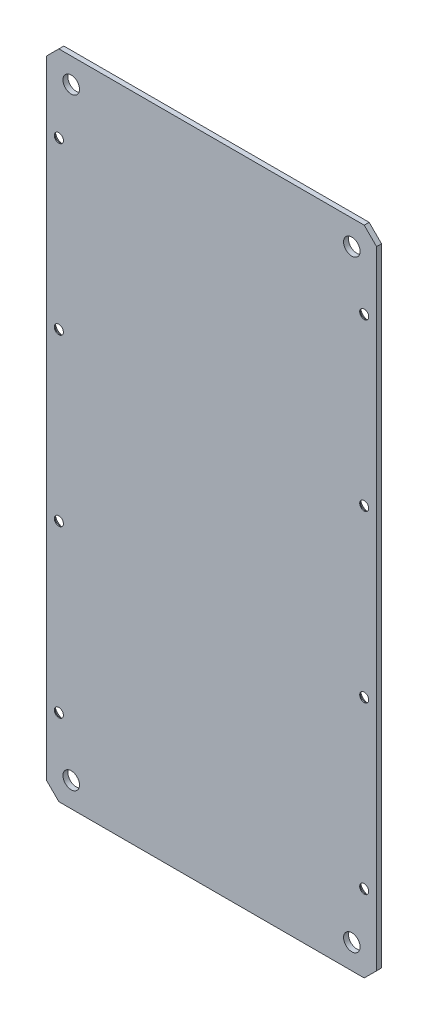
SolidWorks part; units mm, degrees
ref_plane "Спереди" through (0, 0, 0) normal (0, 0, 1) x (1, 0, 0)
ref_plane "Сверху" through (0, 0, 0) normal (0, 1, 0) x (1, 0, 0)
ref_plane "Справа" through (0, 0, 0) normal (1, 0, 0) x (0, 0, -1)
sketch "Эскиз1" plane through (0, 0, 0) normal (0, 0, 1) x (1, 0, 0)
  line L0 (0, 66.6486) -> (0, -35.3582) construction
  line L1 (-169.9255, 0) -> (185.3645, 0) construction
  line L2 (-100, 190) -> (-92.5, 197.5)
  line L3 (-92.5, -197.5) -> (92.5, -197.5)
  line L4 (-100, -190) -> (-100, 190)
  line L5 (-92.5, 197.5) -> (92.5, 197.5)
  line L6 (100, -190) -> (100, 190)
  line L7 (92.5, 197.5) -> (100, 190)
  line L8 (92.5, -197.5) -> (100, -190)
  line L9 (-100, -190) -> (-92.5, -197.5)
  line L10 (-92.5, 0) -> (-92.5, 132.1142) construction
  circle A0 centre (-85, 182.5) radius 5
  circle A1 centre (85, 182.5) radius 5
  circle A2 centre (85, -182.5) radius 5
  circle A3 centre (-85, -182.5) radius 5
  circle A5 centre (-92.5, 150.75) radius 2.75
  circle A6 centre (-92.5, -150.75) radius 2.75
  circle A7 centre (-92.5, 50.25) radius 2.75
  circle A8 centre (-92.5, -50.25) radius 2.75
  circle A9 centre (92.5, 150.75) radius 2.75
  circle A10 centre (92.5, 50.25) radius 2.75
  circle A12 centre (92.5, -50.25) radius 2.75
  circle A13 centre (92.5, -150.75) radius 2.75
  point P5 (-100, -197.5)
  point P6 (100, 197.5)
  point P7 (-100, 197.5)
  point P8 (100, -197.5)
  dimension "D3" = 10
  dimension "D4" = 15
  dimension "D12" = 5.5
  dimension "D13" = 301.5
  dimension "D6" = 100.5
  dimension "D1" = 395
  dimension "D2" = 200
  dimension "D5" = 15
  dimension "D8" = 7.5
  dimension "D9" = 7.5
  dimension "D10" = 7.5
  dimension "D11" = 7.5
  dimension "D15" = 7.5
extrude "Вытянуть1" add sketch "Эскиз1" along normal blind 3
chamfer "Фаска1" distance 2.5 angle 45 8 edges at (-89.75, 150.75, 0) (-89.75, 50.25, 0) (-95.25, -50.25, 0) (-95.25, -150.75, 0) (95.25, -150.75, 0) (95.25, -50.25, 0) (89.75, 50.25, 0) (89.75, 150.75, 0)
